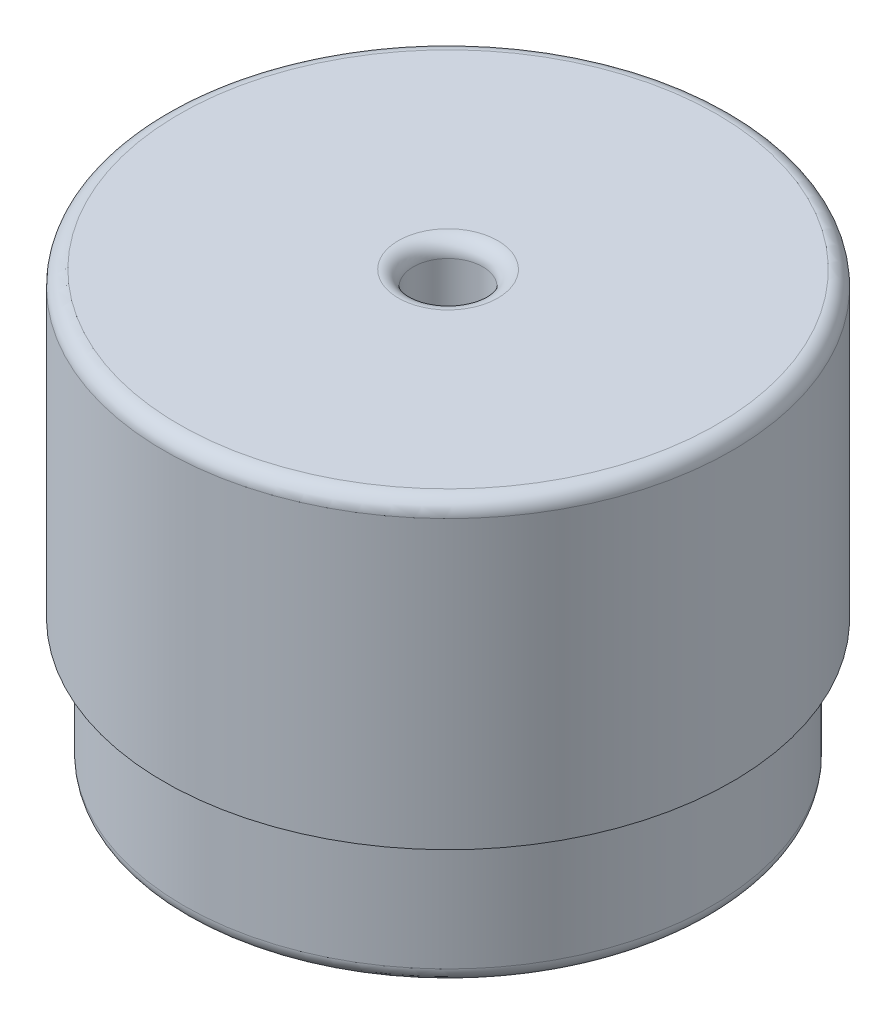
SolidWorks part; units mm, degrees
ref_plane "Front Plane" through (0, 0, 0) normal (0, 0, 1) x (1, 0, 0)
ref_plane "Top Plane" through (0, 0, 0) normal (0, 1, 0) x (1, 0, 0)
ref_plane "Right Plane" through (0, 0, 0) normal (1, 0, 0) x (0, 0, -1)
sketch "Sketch1" plane through (0, 0, 0) normal (0, 0, 1) x (1, 0, 0)
  line L0 (0, 0) -> (0, 30.4) construction
  line L1 (3.4925, -11.8133) -> (3.4925, 28.88)
  line L2 (3.4925, 30.4) -> (128.348, 30.4) construction
  line L3 (3.4925, 30.4) -> (3.4925, 0) construction
  line L4 (3.4925, 0) -> (49.7075, 0) construction
  line L6 (5.0125, 30.4) -> (27.08, 30.4)
  line L8 (5.0125, -13.3333) -> (25.08, -13.3333)
  line L9 (26.6, -11.8133) -> (26.6, -0.5721)
  line L12 (28.6, 28.88) -> (28.6, 0)
  line L13 (27.1721, 0) -> (28.6, 0)
  arc A0 (3.4925, -11.8133) -> (5.0125, -13.3333) centre (5.0125, -11.8133) ccw
  arc A1 (25.08, -13.3333) -> (26.6, -11.8133) centre (25.08, -11.8133) ccw
  arc A3 (3.4925, 28.88) -> (5.0125, 30.4) centre (5.0125, 28.88) cw
  arc A4 (27.08, 30.4) -> (28.6, 28.88) centre (27.08, 28.88) cw
  arc A5 (26.6, -0.5721) -> (27.1721, 0) centre (27.1721, -0.5721) cw
  point P18 (26.6, 0)
  point P27 (26.6, 0)
  dimension "D7" = 1.52
  dimension "D6" = 0.5721
  dimension "D1" = 30.4
  dimension "D2" = 3.4925
  dimension "D5" = 13.3333
  dimension "D3" = 25.1075
  dimension "D4" = 23.1075
revolve "Revolve1" add sketch "Sketch1" angle 360 about L0
equation "\"D1@Sketch1\"=\"Upper_Mount_largest_radius\"/0.875"
equation "\"D2@Sketch1\"=\"Lower_Mount_piston_rod_radius\""
equation "\"D5@Sketch1\"=(\"Upper_Mount_largest_radius\"/1.90909091)-0.6mm"
equation "\"Lower_Mount_piston_rod_radius\"\t=3.4925"
equation "\"Upper_Mount_largest_radius\" =26.6"
equation "\"D3@Sketch1\"=(((2*\"Upper_Mount_largest_radius\")+(\"Upper_mount_wall_thickness\"))/2)-(\"Lower_Mount_piston_rod_radius\")"
equation "\"D4@Sketch1\"=\"Upper_Mount_largest_radius\"-\"Lower_Mount_piston_rod_radius\""
equation "\"D7@Sketch1\"=\"Upper_Mount_largest_radius\"/17.5"
equation "\"Upper_mount_wall_thickness\" =4"
equation "\"Lower_Mount_piston_rod_length\" =149"
equation "\"Piston_orifice_dia\"=0.30711"
equation "\"Spring_inner_dia\" =80"
equation "\"Spring_wire_dia\" =8"
equation "\"D6@Sketch1\"=((((2*\"Upper_Mount_largest_radius\")+(\"Upper_mount_wall_thickness\"))/2)-(\"Lower_Mount_piston_rod_radius\")-1mm)/42.14"
